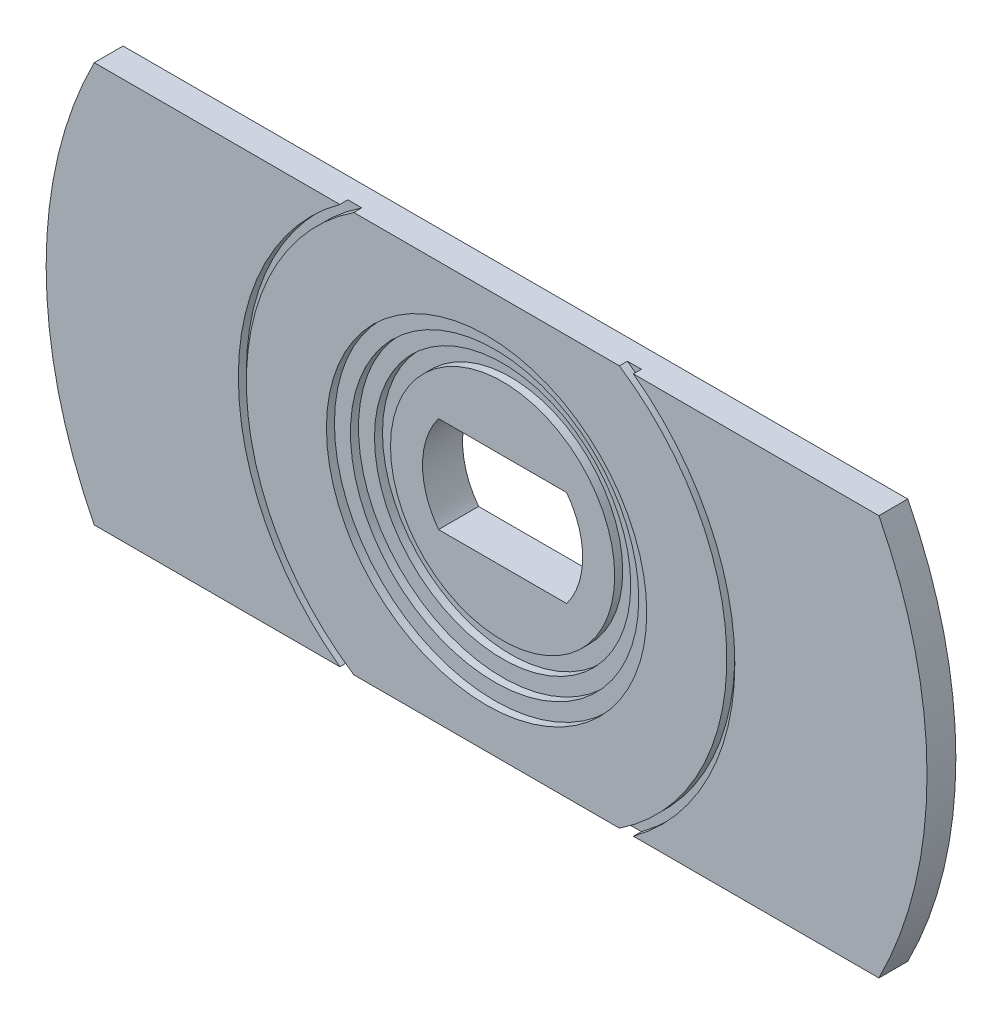
SolidWorks part; units mm, degrees
material "PA Тип 6"
ref_plane "Спереди" through (0, 0, 0) normal (0, 0, 1) x (1, 0, 0)
ref_plane "Сверху" through (0, 0, 0) normal (0, 1, 0) x (1, 0, 0)
ref_plane "Справа" through (0, 0, 0) normal (1, 0, 0) x (0, 0, -1)
sketch "Эскиз1" plane through (0, 0, 0) normal (1, 0, 0) x (0, 0, -1)
  line L0 (0, 29.533) -> (0, -1.8956) construction
  line L1 (-1.4835, 0) -> (10.8242, 0) construction
  line L2 (1.5, 7) -> (1.5, 8)
  line L3 (0, 27.5) -> (1.8, 27.5)
  line L4 (0, 27.5) -> (0, 15.5)
  line L5 (1.5, 7) -> (1.8, 7)
  line L6 (1.8, 27.5) -> (1.8, 7)
  line L7 (1.5, 8) -> (1, 8)
  line L8 (1, 8) -> (1, 9)
  line L9 (1, 9) -> (0.5, 9)
  line L10 (0.5, 9) -> (0.5, 10)
  line L11 (0.5, 10) -> (0, 10)
  line L12 (0, 15) -> (0.5, 15)
  line L13 (0.5, 15) -> (0.5, 15.5)
  line L14 (0.5, 15.5) -> (0, 15.5)
  line L15 (0, 15) -> (0, 10)
  dimension "D1" = 27.5
  dimension "D2" = 7
  dimension "D3" = 1.8
  dimension "D4" = 1
  dimension "D5" = 1
  dimension "D6" = 1
  dimension "D7" = 0.3
  dimension "D8" = 0.5
  dimension "D9" = 0.5
  dimension "D10" = 15
  dimension "D11" = 0.5
  dimension "D12" = 0.5
revolve "Повернуть1" add sketch "Эскиз1" angle 360 about L1
sketch "Эскиз2" plane through (0, 0, 0) normal (0, 0, 1) x (1, 0, 0)
  line L0 (-29.2418, 0) -> (30.9384, 0) construction
  line L1 (-24.4949, 12.5) -> (24.4949, 12.5)
  line L2 (-24.4949, -12.5) -> (24.4949, -12.5)
  circle A1 centre (0, 0) radius 27.5 construction
  circle A2 centre (0, 0) radius 27.5
  arc A3 (-24.4949, -12.5) -> (24.4949, -12.5) centre (0, 0) ccw
  arc A4 (24.4949, 12.5) -> (-24.4949, 12.5) centre (0, 0) ccw
  dimension "D2" = 12.5
  dimension "D1" = 0
extrude "Вырез-Вытянуть1" cut sketch "Эскиз2" against normal up to surface (1.8 mm away) up to face at (27.5, 0, -1.8)
sketch "Эскиз3" plane through (0, 0, -1.5) normal (0, 0, 1) x (1, 0, 0)
  line L0 (-29.421, 0) -> (31.1947, 0) construction
  line L1 (4, 3) -> (-4, 3)
  line L2 (4, -3) -> (-4, -3)
  circle A2 centre (0, 0) radius 5
  arc A3 (-4, 3) -> (-4, -3) centre (0, 0) ccw
  arc A4 (4, -3) -> (4, 3) centre (0, 0) ccw
  circle A5 centre (0, 0) radius 7
  circle A6 centre (0, 0) radius 7
  dimension "D3" = 3
  dimension "D1" = 2
  dimension "D2" = 0
extrude "Бобышка-Вытянуть1" add sketch "Эскиз3" against normal blind 2 and the other way blind 0.5
